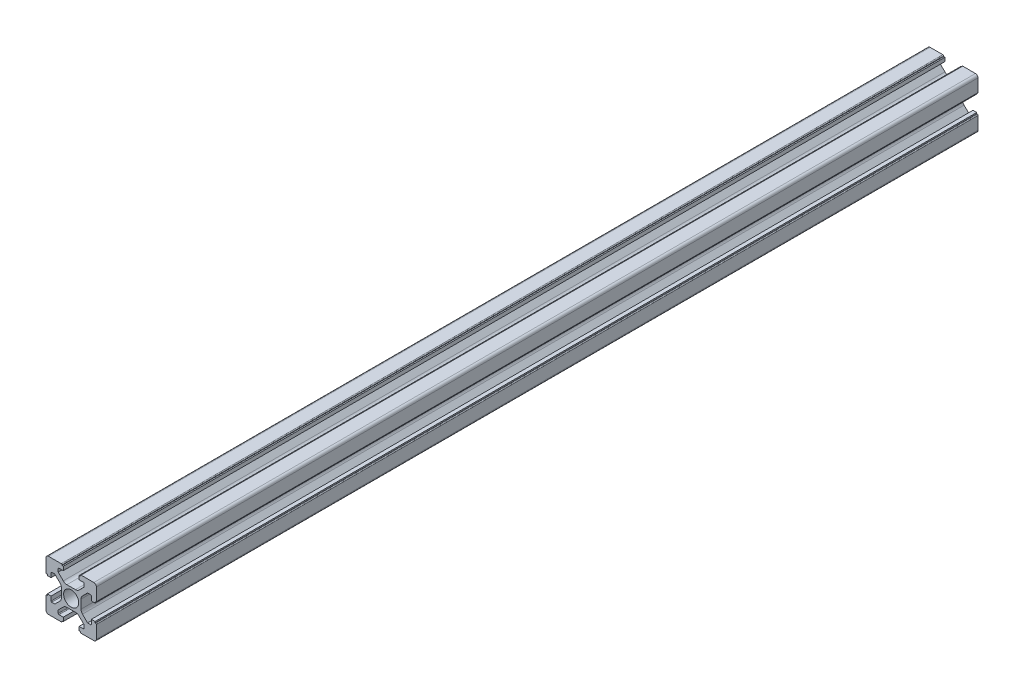
SolidWorks part; units mm, degrees
material "6061-T6 (SS)"
ref_plane "前视基准面" through (0, 0, 0) normal (0, 0, 1) x (1, 0, 0)
ref_plane "上视基准面" through (0, 0, 0) normal (0, 1, 0) x (1, 0, 0)
ref_plane "右视基准面" through (0, 0, 0) normal (1, 0, 0) x (0, 0, -1)
sketch "草图1" plane through (0, 0, 0) normal (0, 0, 1) x (1, 0, 0)
  line L0 (0, -3.9) -> (0, 3.9) construction
  line L1 (-10, -9) -> (-10, -3.95)
  line L2 (-3.9, 0) -> (3.9, 0) construction
  line L3 (-9.7, -3.65) -> (-9.5, -3.65)
  line L5 (-9.5, -3.65) -> (-9.5, -3.15)
  line L7 (-9.5, -3.15) -> (-8, -3.15)
  line L9 (-8, -3.15) -> (-8, -4.85)
  line L11 (-7.7, -5.15) -> (-6.5, -5.15)
  line L13 (-6.5, -5.15) -> (-4.4858, -3.1358)
  line L15 (-3.9, -1.7216) -> (-3.9, 1.7216)
  line L17 (-6.5, 5.15) -> (-4.4858, 3.1358)
  line L19 (-7.7, 5.15) -> (-6.5, 5.15)
  line L21 (-8, 3.15) -> (-8, 4.85)
  line L23 (-9.5, 3.15) -> (-8, 3.15)
  line L25 (-9.5, 3.65) -> (-9.5, 3.15)
  line L27 (-9.7, 3.65) -> (-9.5, 3.65)
  line L29 (-10, 9) -> (-10, 3.95)
  line L31 (-9, 10) -> (-3.95, 10)
  line L33 (-3.65, 9.7) -> (-3.65, 9.5)
  line L35 (-3.65, 9.5) -> (-3.15, 9.5)
  line L37 (-3.15, 9.5) -> (-3.15, 8)
  line L39 (-3.15, 8) -> (-4.85, 8)
  line L41 (-5.15, 7.7) -> (-5.15, 6.5)
  line L43 (-5.15, 6.5) -> (-3.1358, 4.4858)
  line L45 (1.7216, 3.9) -> (-1.7216, 3.9)
  line L47 (5.15, 6.5) -> (3.1358, 4.4858)
  line L49 (5.15, 7.7) -> (5.15, 6.5)
  line L51 (3.15, 8) -> (4.85, 8)
  line L53 (3.15, 9.5) -> (3.15, 8)
  line L55 (3.65, 9.5) -> (3.15, 9.5)
  line L57 (3.65, 9.7) -> (3.65, 9.5)
  line L59 (9, 10) -> (3.95, 10)
  line L61 (10, 9) -> (10, 3.95)
  line L63 (9.7, 3.65) -> (9.5, 3.65)
  line L65 (9.5, 3.65) -> (9.5, 3.15)
  line L67 (9.5, 3.15) -> (8, 3.15)
  line L69 (8, 3.15) -> (8, 4.85)
  line L71 (7.7, 5.15) -> (6.5, 5.15)
  line L73 (6.5, 5.15) -> (4.4858, 3.1358)
  line L75 (3.9, 1.7216) -> (3.9, -1.7216)
  line L77 (6.5, -5.15) -> (4.4858, -3.1358)
  line L79 (7.7, -5.15) -> (6.5, -5.15)
  line L81 (8, -3.15) -> (8, -4.85)
  line L83 (9.5, -3.15) -> (8, -3.15)
  line L85 (9.5, -3.65) -> (9.5, -3.15)
  line L87 (9.7, -3.65) -> (9.5, -3.65)
  line L89 (10, -9) -> (10, -3.95)
  line L91 (9, -10) -> (3.95, -10)
  line L93 (3.65, -9.7) -> (3.65, -9.5)
  line L95 (3.65, -9.5) -> (3.15, -9.5)
  line L97 (3.15, -9.5) -> (3.15, -8)
  line L99 (3.15, -8) -> (4.85, -8)
  line L101 (5.15, -7.7) -> (5.15, -6.5)
  line L103 (5.15, -6.5) -> (3.1358, -4.4858)
  line L105 (-1.7216, -3.9) -> (1.7216, -3.9)
  line L107 (-5.15, -6.5) -> (-3.1358, -4.4858)
  line L109 (-5.15, -7.7) -> (-5.15, -6.5)
  line L111 (-3.15, -8) -> (-4.85, -8)
  line L113 (-3.15, -9.5) -> (-3.15, -8)
  line L115 (-3.65, -9.5) -> (-3.15, -9.5)
  line L117 (-3.65, -9.7) -> (-3.65, -9.5)
  line L119 (-9, -10) -> (-3.95, -10)
  circle A0 centre (0, 0) radius 3
  ellipse E3 centre (-9, -9) end of major axis (-10, -9) minor radius 1 (-10, -9) -> (-9, -10) ccw
  ellipse E5 centre (-9.7, -3.95) end of major axis (-10, -3.95) minor radius 0.3 (-9.7, -3.65) -> (-10, -3.95) ccw
  ellipse E7 centre (-7.7, -4.85) end of major axis (-7.4, -4.85) minor radius 0.3 (-8, -4.85) -> (-7.7, -5.15) ccw
  ellipse E9 centre (-5.9, -1.7216) end of major axis (-5.9, -3.7216) minor radius 2 (-4.4858, -3.1358) -> (-3.9, -1.7216) ccw
  ellipse E11 centre (-5.9, 1.7216) end of major axis (-3.9, 1.7216) minor radius 2 (-3.9, 1.7216) -> (-4.4858, 3.1358) ccw
  ellipse E13 centre (-7.7, 4.85) end of major axis (-7.4, 4.85) minor radius 0.3 (-7.7, 5.15) -> (-8, 4.85) ccw
  ellipse E15 centre (-9.7, 3.95) end of major axis (-9.4, 3.95) minor radius 0.3 (-10, 3.95) -> (-9.7, 3.65) ccw
  ellipse E17 centre (-9, 9) end of major axis (-10, 9) minor radius 1 (-9, 10) -> (-10, 9) ccw
  ellipse E19 centre (-3.95, 9.7) end of major axis (-3.65, 9.7) minor radius 0.3 (-3.65, 9.7) -> (-3.95, 10) ccw
  ellipse E21 centre (-4.85, 7.7) end of major axis (-4.55, 7.7) minor radius 0.3 (-4.85, 8) -> (-5.15, 7.7) ccw
  ellipse E23 centre (-1.7216, 5.9) end of major axis (0.2784, 5.9) minor radius 2 (-3.1358, 4.4858) -> (-1.7216, 3.9) ccw
  ellipse E25 centre (1.7216, 5.9) end of major axis (3.7216, 5.9) minor radius 2 (1.7216, 3.9) -> (3.1358, 4.4858) ccw
  ellipse E27 centre (4.85, 7.7) end of major axis (4.85, 8) minor radius 0.3 (5.15, 7.7) -> (4.85, 8) ccw
  ellipse E29 centre (3.95, 9.7) end of major axis (3.95, 10) minor radius 0.3 (3.95, 10) -> (3.65, 9.7) ccw
  ellipse E31 centre (9, 9) end of major axis (10, 9) minor radius 1 (10, 9) -> (9, 10) ccw
  ellipse E33 centre (9.7, 3.95) end of major axis (10, 3.95) minor radius 0.3 (9.7, 3.65) -> (10, 3.95) ccw
  ellipse E35 centre (7.7, 4.85) end of major axis (8, 4.85) minor radius 0.3 (8, 4.85) -> (7.7, 5.15) ccw
  ellipse E37 centre (5.9, 1.7216) end of major axis (7.9, 1.7216) minor radius 2 (4.4858, 3.1358) -> (3.9, 1.7216) ccw
  ellipse E39 centre (5.9, -1.7216) end of major axis (7.9, -1.7216) minor radius 2 (3.9, -1.7216) -> (4.4858, -3.1358) ccw
  ellipse E41 centre (7.7, -4.85) end of major axis (8, -4.85) minor radius 0.3 (7.7, -5.15) -> (8, -4.85) ccw
  ellipse E43 centre (9.7, -3.95) end of major axis (10, -3.95) minor radius 0.3 (10, -3.95) -> (9.7, -3.65) ccw
  ellipse E45 centre (9, -9) end of major axis (10, -9) minor radius 1 (9, -10) -> (10, -9) ccw
  ellipse E47 centre (3.95, -9.7) end of major axis (3.95, -9.4) minor radius 0.3 (3.65, -9.7) -> (3.95, -10) ccw
  ellipse E49 centre (4.85, -7.7) end of major axis (4.85, -7.4) minor radius 0.3 (4.85, -8) -> (5.15, -7.7) ccw
  ellipse E51 centre (1.7216, -5.9) end of major axis (1.7216, -7.9) minor radius 2 (3.1358, -4.4858) -> (1.7216, -3.9) ccw
  ellipse E53 centre (-1.7216, -5.9) end of major axis (-1.7216, -3.9) minor radius 2 (-1.7216, -3.9) -> (-3.1358, -4.4858) ccw
  ellipse E55 centre (-4.85, -7.7) end of major axis (-4.55, -7.7) minor radius 0.3 (-5.15, -7.7) -> (-4.85, -8) ccw
  ellipse E57 centre (-3.95, -9.7) end of major axis (-3.65, -9.7) minor radius 0.3 (-3.95, -10) -> (-3.65, -9.7) ccw
  dimension "D2" = 20
extrude "凸台-拉伸1" add sketch "草图1" along normal blind 350
